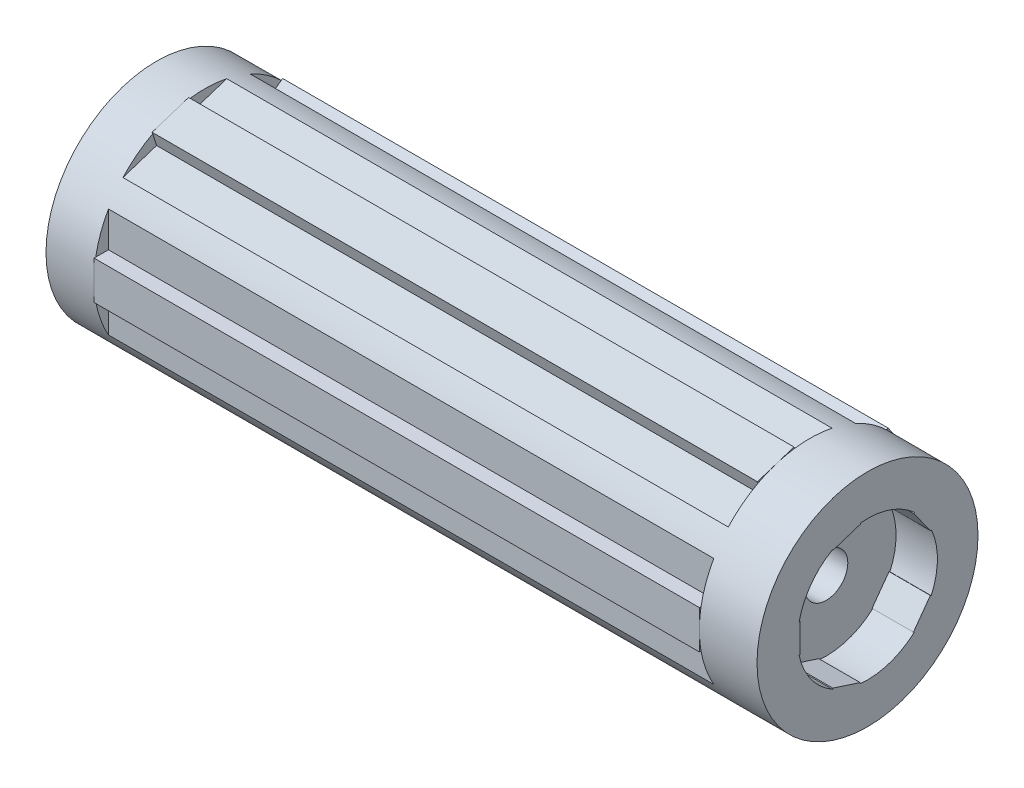
SolidWorks part; units mm, degrees
material "PVC hart"
ref_plane "Ebene vorne" through (0, 0, 0) normal (0, 0, 1) x (1, 0, 0)
ref_plane "Ebene oben" through (0, 0, 0) normal (0, 1, 0) x (1, 0, 0)
ref_plane "Ebene rechts" through (0, 0, 0) normal (1, 0, 0) x (0, 0, -1)
sketch "Skizze1" plane through (0, 0, 0) normal (1, 0, 0) x (0, 0, -1)
  circle A0 centre (0, 0) radius 11.5
  dimension "D1" = 23
extrude "Grundkörper Walze" add sketch "Skizze1" along normal blind 74
sketch "Skizze2" plane through (74, 0, 0) normal (1, 0, 0) x (0, 0, -1)
  line L0 (-15.3822, 0) -> (15.9559, 0) construction
  line L1 (-7.1138, 1.523) -> (-7.0138, 1.523)
  line L2 (-7.0138, 1.523) -> (-7.0138, -1.477)
  line L3 (-7.0138, -1.477) -> (-7.1235, -1.477)
  line L4 (-0.7498, 7.2363) -> (-0.7189, 7.1412)
  line L5 (-0.7189, 7.1412) -> (-3.5721, 6.2141)
  line L6 (-3.5721, 6.2141) -> (-3.606, 6.3184)
  line L7 (6.6504, 2.9492) -> (6.5695, 2.8905)
  line L8 (6.5695, 2.8905) -> (4.8061, 5.3175)
  line L9 (4.8061, 5.3175) -> (4.8949, 5.382)
  line L10 (4.86, -5.4135) -> (4.7791, -5.3548)
  line L11 (4.7791, -5.3548) -> (6.5424, -2.9277)
  line L12 (6.5424, -2.9277) -> (6.6312, -2.9922)
  line L13 (-3.6468, -6.295) -> (-3.6159, -6.1999)
  line L14 (-3.6159, -6.1999) -> (-0.7627, -7.1269)
  line L15 (-0.7627, -7.1269) -> (-0.7966, -7.2313)
  arc A0 (-7.1235, -1.477) -> (-3.6468, -6.295) centre (0, 0) ccw
  arc A1 (-3.606, 6.3184) -> (-7.1138, 1.523) centre (0, 0) ccw
  arc A2 (4.8949, 5.382) -> (-0.7498, 7.2363) centre (0, 0) ccw
  arc A3 (6.6312, -2.9922) -> (6.6504, 2.9492) centre (0, 0) ccw
  arc A4 (-0.7966, -7.2313) -> (4.86, -5.4135) centre (0, 0) ccw
  point P28 (0, 0)
  dimension "D1" = 14.55
  dimension "D2" = 3
  dimension "D3" = 0.1
  dimension "D4" = 5
extrude "Presspassung Kugellager" cut sketch "Skizze2" against normal blind 4.3
sketch "Skizze3" plane through (69.7, 0, 0) normal (1, 0, 0) x (0, 0, -1)
  circle A0 centre (0, 0) radius 2.25
  dimension "D1" = 4.5
extrude "M4 Schraubenführung" cut sketch "Skizze3" against normal blind 4.5
sketch "Skizze4" plane through (0, 0, 0) normal (-1, 0, 0) x (0, 0, 1)
  circle A0 centre (0, 0) radius 9.675
  dimension "D1" = 19.35
extrude "Motoraussparung " cut sketch "Skizze4" against normal blind 12.75
sketch "Skizze7" plane through (74, 0, 0) normal (1, 0, 0) x (0, 0, -1)
  line L0 (0, 13.4409) -> (0, -14.2481) construction
  line L1 (-11.5, 7.5) -> (-10, 7.5)
  line L2 (-11.5, 7.5) -> (-11.5, -7.5)
  line L3 (-11.5, -7.5) -> (-10, -7.5)
  line L4 (-10, 7.5) -> (-10, -7.5)
  dimension "D1" = 1.5
  dimension "D2" = 15
  dimension "D3" = 10
extrude "Zerstörungselement Aussparung" cut sketch "Skizze7" against normal blind 63 from offset 6 offset against normal yes
sketch "Skizze8" plane through (0, 0, 10) normal (0, 0, 1) x (1, 0, 0)
  line L0 (68, -5.6789) -> (68, 5.6789) construction
  line L1 (5, 2) -> (68, 2)
  line L2 (5, 2) -> (5, -2)
  line L3 (5, -2) -> (68, -2)
  line L4 (68, 2) -> (68, -2)
  line L5 (5, 2) -> (68, -2) construction
  line L6 (5, -2) -> (68, 2) construction
  line L7 (12.65, 0) -> (-12.65, 0) construction
  point P0 (36.5, 0)
  dimension "D1" = 31.5
  dimension "D3" = 63
  dimension "D4" = 4
extrude "Zerstörungselement Rechteck" add sketch "Skizze8" along normal blind 1.5
sketch "Skizze10" plane through (12.75, 0, 0) normal (-1, 0, 0) x (0, 0, 1)
  line L1 (4.1398, -2.2968) -> (4.059, 2.4368)
  line L2 (4.059, 2.4368) -> (-0.0809, 4.7336)
  line L3 (-0.0809, 4.7336) -> (-4.1398, 2.2968)
  line L4 (-4.1398, 2.2968) -> (-4.059, -2.4368)
  line L5 (-4.059, -2.4368) -> (0.0809, -4.7336)
  line L6 (0.0809, -4.7336) -> (4.1398, -2.2968)
  circle A0 centre (0, 0) radius 4.1 construction
  dimension "D1" = 8.2
extrude "M5 Motor Mutter " cut sketch "Skizze10" against normal blind 12
sketch "Skizze12" plane through (24.75, 0, 0) normal (-1, 0, 0) x (0, 0, 1)
  circle A0 centre (0, 0) radius 3.1
  dimension "D1" = 6.2
extrude "M5 Auslauf Schraube" cut sketch "Skizze12" against normal blind 2
pattern_circular "Zerstörungselement Vervielfältigung" count 5 over 360 about axis through (0, 0, 0) along (1, 0, 0) of "Zerstörungselement Rechteck", "Zerstörungselement Aussparung"
sketch "Skizze15" plane through (0, 0, 0) normal (0, 0, 1) x (1, 0, 0)
  line L0 (-6.8939, 0) -> (81.9813, 0) construction
  line L1 (27.25, 0) -> (35.75, 8.5)
  line L2 (35.75, 8.5) -> (65.2, 8.5)
  line L3 (65.2, 8.5) -> (65.2, 0)
  line L4 (65.2, -2.25) -> (65.2, 2.25) construction
  line L5 (65.2, 0) -> (27.25, 0)
  line L8 (26.75, 3.1) -> (26.75, -3.1) construction
  dimension "D1" = 8.5
  dimension "D2" = 45
  dimension "D3" = 0.5
revolve "Innenaussparung" cut sketch "Skizze15" angle 360 about L0
chamfer "Fase1" distance 0.4 angle 45 1 edges at (0, 0, 9.675)
